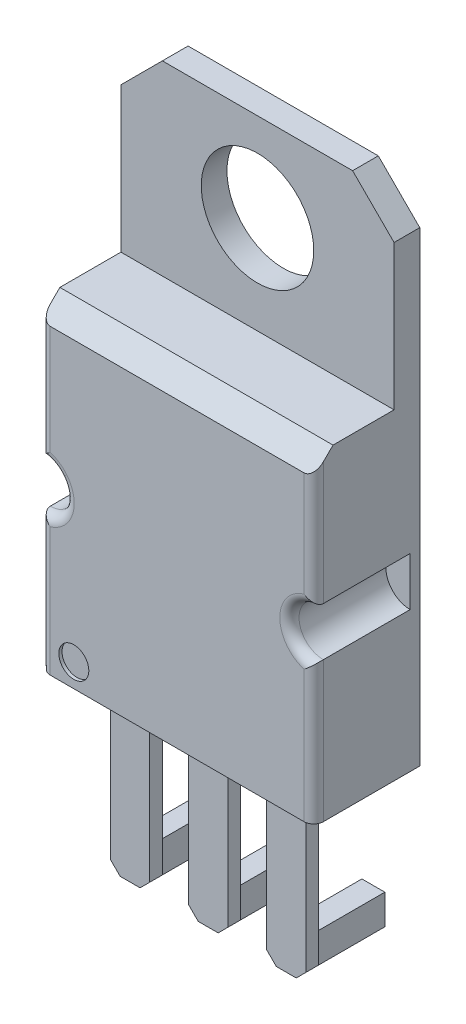
SolidWorks part; units mm, degrees
ref_plane "Alzado" through (0, 0, 0) normal (0, 0, 1) x (1, 0, 0)
ref_plane "Planta" through (0, 0, 0) normal (0, 1, 0) x (1, 0, 0)
ref_plane "Vista lateral" through (0, 0, 0) normal (1, 0, 0) x (0, 0, -1)
sketch "Croquis1" plane through (0, 0, 0) normal (0, 0, 1) x (1, 0, 0)
  line L1 (4.25, 5) -> (-4.25, 5)
  line L2 (4.25, 5) -> (4.25, -5)
  line L3 (4.25, -5) -> (-4.25, -5)
  line L4 (-4.25, 5) -> (-4.25, -5)
  line L5 (4.25, 5) -> (-4.25, -5) construction
  line L6 (4.25, -5) -> (-4.25, 5) construction
  point P0 (0, 0)
  dimension "D1" = 10
  dimension "D2" = 8.5
extrude "Saliente-Extruir1" add sketch "Croquis1" along normal blind 3.3
sketch "Croquis2" plane through (0, 0, 3.3) normal (0, 0, 1) x (1, 0, 0)
  circle A0 centre (-3.2159, -4.2802) radius 0.4667
extrude "Cortar-Extruir1" cut sketch "Croquis2" against normal blind 0.1
sketch "Croquis3" plane through (0, 0, 3.3) normal (0, 0, 1) x (1, 0, 0)
  line L2 (-4.25, 5) -> (-4.25, -5) construction
  line L3 (-4.25, 0.7464) -> (-4.25, -0.7464)
  arc A0 (-4.25, 0.7464) -> (-4.25, -0.7464) centre (-4.25, 0) cw
extrude "Cortar-Extruir2" cut sketch "Croquis3" against normal blind 3
sketch "Croquis4" plane through (0, 0, 3.3) normal (0, 0, 1) x (1, 0, 0)
  line L0 (4.25, -5) -> (4.25, 5) construction
  line L1 (4.25, 0.8787) -> (4.25, -0.6331)
  arc A0 (4.25, 0.8787) -> (4.25, -0.6331) centre (4.25, 0.1228) ccw
extrude "Cortar-Extruir3" cut sketch "Croquis4" against normal blind 3
chamfer "Chaflán1" distance 0.6 angle 45 1 edges at (0, 5, 3.3)
fillet "Redondeo1" radius 0.3 6 edges at (-4.25, 2.5732, 3.3) (-3.5036, 0, 3.3) (-4.25, -2.8732, 3.3) (4.25, -2.8165, 3.3) (3.4941, 0.1228, 3.3) (4.25, 2.6394, 3.3)
sketch "Croquis5" plane through (0, 5, 0) normal (0, 1, 0) x (1, 0, 0)
  line L0 (-4.25, -2.7) -> (-4.25, 0) construction
  line L1 (4.25, 0) -> (-4.25, 0)
  line L2 (4.25, 0) -> (4.25, -0.8)
  line L3 (4.25, -0.8) -> (-4.25, -0.8)
  line L4 (-4.25, 0) -> (-4.25, -0.8)
  dimension "D1" = 0.8
extrude "Saliente-Extruir2" add sketch "Croquis5" along normal blind 5.8
sketch "Croquis6" plane through (0, 0, 0.8) normal (0, 0, 1) x (1, 0, 0)
  line L0 (0, 10.8) -> (0, 5) construction
  line L1 (-4.25, 10.8) -> (4.25, 10.8) construction
  line L2 (-4.25, 5) -> (4.25, 5) construction
  line L3 (-4.25, 10.8) -> (-4.25, 9.8033) construction
  line L4 (-4.25, 10.8) -> (-4.25, 5) construction
  line L5 (-4.25, 9.8033) -> (4.25, 9.8033) construction
  line L6 (4.25, 10.8) -> (4.25, 5) construction
  line L7 (4.25, 9.8033) -> (4.25, 8.042) construction
  line L8 (4.25, 8.042) -> (0, 8.042) construction
  line L9 (0, 8.042) -> (-4.25, 8.042) construction
  circle A0 centre (0, 8.042) radius 1.7505
extrude "Cortar-Extruir4" cut sketch "Croquis6" against normal blind 5.8
sketch "Croquis7" plane through (0, -5, 0) normal (0, -1, 0) x (1, 0, 0)
  line L0 (-4.25, 0) -> (-4.25, 1.9424) construction
  line L1 (-4.25, 3) -> (-4.25, 0) construction
  line L2 (-4.25, 1.9424) -> (4.25, 1.9424) construction
  line L3 (4.25, 3) -> (4.25, 0) construction
  line L4 (-4.25, 1.9424) -> (-4.25, 2.3342) construction
  line L5 (-4.25, 2.3342) -> (4.25, 2.3342) construction
  line L6 (0, 3.3) -> (0, 0) construction
  line L7 (-3.95, 3.3) -> (3.95, 3.3) construction
  line L8 (-4.25, 2.1383) -> (4.25, 2.1383) construction
  line L10 (-0.61, 1.9424) -> (0.61, 1.9424)
  line L11 (-0.61, 1.9424) -> (-0.61, 2.3342)
  line L12 (-0.61, 2.3342) -> (0.61, 2.3342)
  line L13 (0.61, 1.9424) -> (0.61, 2.3342)
  line L14 (-0.61, 1.9424) -> (0.61, 2.3342) construction
  line L15 (-0.61, 2.3342) -> (0.61, 1.9424) construction
  point P17 (0, 2.1383)
  dimension "D1" = 1.22
extrude "Saliente-Extruir3" add sketch "Croquis7" along normal blind 5.3
sketch "Croquis8" plane through (0, -5, 0) normal (0, -1, 0) x (1, 0, 0)
  line L0 (0.61, 2.1383) -> (4.25, 2.1383) construction
  line L1 (0.61, 1.9424) -> (0.61, 2.3342) construction
  line L2 (4.25, 3) -> (4.25, 0) construction
  line L3 (-0.61, 2.1383) -> (-4.25, 2.1383) construction
  line L4 (-0.61, 2.3342) -> (-0.61, 1.9424) construction
  line L5 (-4.25, 3) -> (-4.25, 0) construction
  line L6 (-4.25, 2.1383) -> (-4.25, 2.3342) construction
  line L7 (-4.25, 2.3342) -> (-4.25, 1.9424) construction
  line L8 (-4.25, 1.9424) -> (-0.61, 1.9424) construction
  line L9 (-0.61, 2.3342) -> (-0.61, 1.9424) construction
  line L10 (-0.61, 1.9424) -> (-0.61, 2.3342) construction
  line L11 (-0.61, 2.3342) -> (-4.25, 2.3342) construction
  line L12 (-4.25, 2.3342) -> (4.25, 2.3342) construction
  line L13 (4.25, 2.3342) -> (4.25, 1.9424) construction
  line L14 (4.25, 1.9424) -> (0.61, 1.9424) construction
  line L15 (-0.61, 1.9424) -> (0.61, 1.9424) construction
  line L16 (-0.61, 1.9424) -> (0.61, 1.9424) construction
  line L17 (0.61, 1.9424) -> (0.61, 2.3342) construction
  line L18 (0.61, 2.3342) -> (0.61, 3.3) construction
  line L19 (-3.95, 3.3) -> (3.95, 3.3) construction
  line L20 (0.61, 3.3) -> (4.25, 2.3342) construction
  line L21 (4.25, 2.3342) -> (4.1621, 3.2121) construction
  line L22 (4.1621, 3.2121) -> (0.61, 2.3342) construction
  line L23 (0.61, 2.3342) -> (-0.61, 2.3342) construction
  line L24 (-0.61, 2.3342) -> (-4.1621, 3.2121) construction
  line L25 (-4.1621, 3.2121) -> (-4.25, 2.3342) construction
  line L26 (-4.25, 2.3342) -> (-0.61, 2.3342) construction
  line L27 (-0.61, 2.3342) -> (-0.61, 3.3) construction
  line L28 (-0.61, 3.3) -> (-4.25, 2.3342) construction
  line L29 (-4.25, 2.3342) -> (-2.3861, 2.7732) construction
  line L30 (-2.3861, 2.7732) -> (-2.43, 1.9424) construction
  line L31 (-2.43, 1.9424) -> (2.43, 2.8171) construction
  line L32 (2.43, 2.8171) -> (2.43, 1.9424) construction
  line L34 (3.04, 2.3342) -> (1.82, 2.3342)
  line L35 (3.04, 2.3342) -> (3.04, 1.9424)
  line L36 (3.04, 1.9424) -> (1.82, 1.9424)
  line L37 (1.82, 2.3342) -> (1.82, 1.9424)
  line L38 (3.04, 2.3342) -> (1.82, 1.9424) construction
  line L39 (3.04, 1.9424) -> (1.82, 2.3342) construction
  line L40 (-1.82, 2.3342) -> (-3.04, 2.3342)
  line L41 (-1.82, 2.3342) -> (-1.82, 1.9424)
  line L42 (-1.82, 1.9424) -> (-3.04, 1.9424)
  line L43 (-3.04, 2.3342) -> (-3.04, 1.9424)
  line L44 (-1.82, 2.3342) -> (-3.04, 1.9424) construction
  line L45 (-1.82, 1.9424) -> (-3.04, 2.3342) construction
  arc A0 (4.25, 3) -> (3.95, 3.3) centre (3.95, 3) ccw construction
  arc A1 (-3.95, 3.3) -> (-4.25, 3) centre (-3.95, 3) ccw construction
  point P12 (2.43, 2.1383)
  point P48 (-2.43, 2.1383)
  dimension "D1" = 1.22
  dimension "D2" = 1.22
extrude "Saliente-Extruir4" add sketch "Croquis8" along normal blind 5.3
sketch "Croquis9" plane through (0, 0, 1.9424) normal (0, 0, -1) x (-1, 0, 0)
  line L0 (0, -10.3) -> (0, -9.3) construction
  line L1 (0.61, -10.3) -> (-0.61, -10.3) construction
  line L2 (0, -9.3) -> (0.61, -9.3) construction
  line L3 (0.61, -10.3) -> (0.61, -5) construction
  line L4 (0.61, -9.3) -> (3.04, -9.3) construction
  line L5 (3.04, -10.3) -> (3.04, -5) construction
  line L6 (-1.82, -9.3) -> (-3.04, -9.3) construction
  line L7 (-1.82, -10.3) -> (-1.82, -5) construction
  line L8 (-3.04, -10.3) -> (-3.04, -5) construction
  line L9 (-2.43, -9.3) -> (-2.43, -10.3) construction
  line L10 (-1.82, -10.3) -> (-3.04, -10.3) construction
  line L11 (2.43, -10.3) -> (2.43, -9.3) construction
  line L12 (3.04, -10.3) -> (1.82, -10.3) construction
  line L14 (0.305, -9.3) -> (-0.3707, -9.3)
  line L15 (0.305, -9.3) -> (0.305, -10.3)
  line L16 (0.305, -10.3) -> (-0.3707, -10.3)
  line L17 (-0.3707, -9.3) -> (-0.3707, -10.3)
  line L18 (2.7169, -9.3) -> (2.0972, -9.3)
  line L19 (2.7169, -9.3) -> (2.7169, -10.3)
  line L20 (2.7169, -10.3) -> (2.0972, -10.3)
  line L21 (2.0972, -9.3) -> (2.0972, -10.3)
  line L22 (-2.0916, -9.3) -> (-2.8054, -9.3)
  line L23 (-2.0916, -9.3) -> (-2.0916, -10.3)
  line L24 (-2.0916, -10.3) -> (-2.8054, -10.3)
  line L25 (-2.8054, -9.3) -> (-2.8054, -10.3)
  dimension "D1" = 1
extrude "Saliente-Extruir5" add sketch "Croquis9" along normal blind 2.3
chamfer "Chaflán2" distance 0.3 angle 45 1 edges at (3.04, -10.3, 2.1383)
chamfer "Chaflán3" distance 0.3 angle 45 1 edges at (1.82, -10.3, 2.1383)
chamfer "Chaflán4" distance 0.3 angle 45 1 edges at (-0.61, -10.3, 2.1383)
chamfer "Chaflán5" distance 0.3 angle 45 1 edges at (-3.04, -10.3, 2.1383)
chamfer "Chaflán6" distance 0.3 angle 45 1 edges at (-1.82, -10.3, 2.1383)
chamfer "Chaflán7" distance 0.3 angle 45 1 edges at (0.61, -10.3, 2.1383)
chamfer "Chaflán8" distance 1.29 angle 45 1 edges at (4.25, 10.8, 0.4)
chamfer "Chaflán9" distance 1.29 angle 45 1 edges at (-4.25, 10.8, 0.4)
